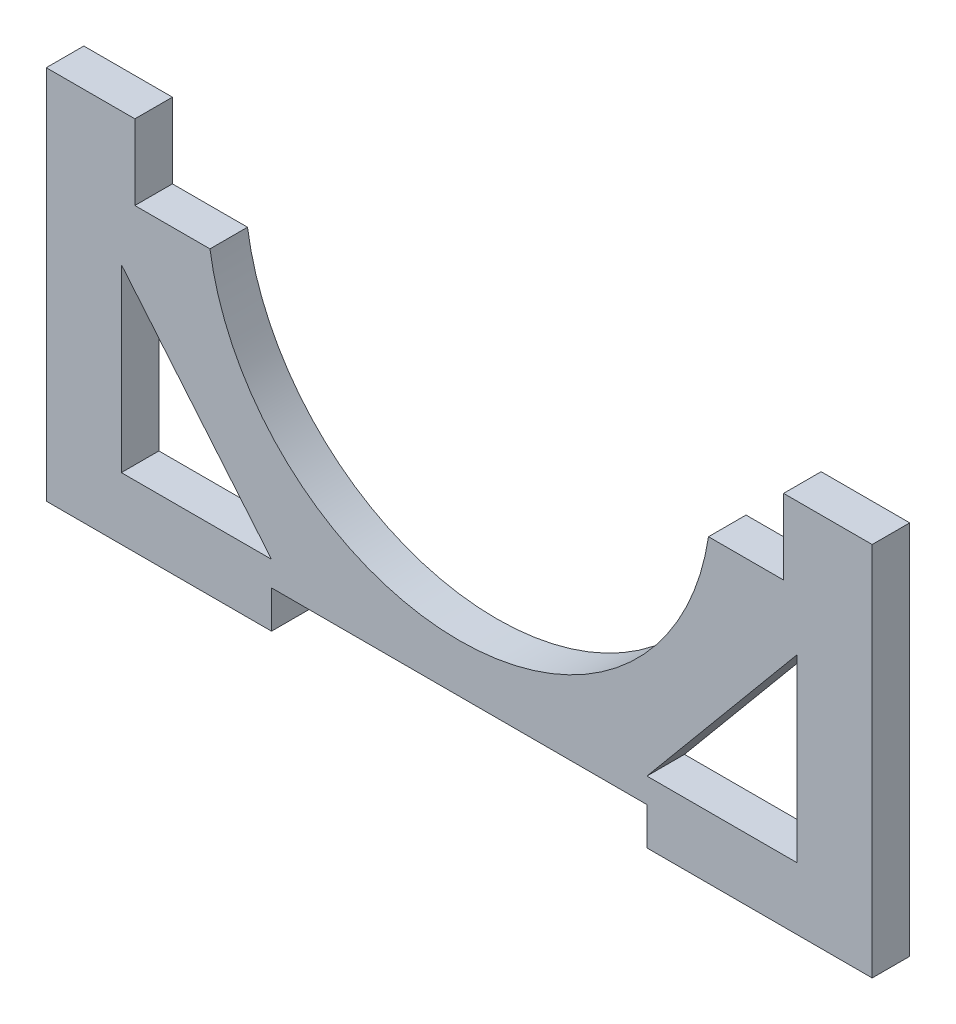
SolidWorks part; units mm, degrees
ref_plane "Front" through (0, 0, 0) normal (0, 0, 1) x (1, 0, 0)
ref_plane "Top" through (0, 0, 0) normal (0, 1, 0) x (1, 0, 0)
ref_plane "Right" through (0, 0, 0) normal (1, 0, 0) x (0, 0, -1)
sketch "Sketch1" plane through (0, 0, 0) normal (0, 0, 1) x (1, 0, 0)
  line L0 (-34.925, 28.575) -> (-34.925, -3.175)
  line L1 (-34.925, -3.175) -> (-15.875, -3.175)
  line L2 (-15.875, -3.175) -> (-15.875, 0)
  line L3 (-15.875, 0) -> (15.875, 0)
  line L4 (15.875, 0) -> (15.875, -3.175)
  line L5 (15.875, -3.175) -> (34.925, -3.175)
  line L6 (34.925, -3.175) -> (34.925, 28.575)
  line L7 (-34.925, 28.575) -> (-27.432, 28.575)
  line L8 (-27.432, 28.575) -> (-27.432, 22.225)
  line L9 (34.925, 28.575) -> (27.432, 28.575)
  line L10 (27.432, 28.575) -> (27.432, 22.225)
  line L11 (-27.432, 22.225) -> (27.432, 22.225)
  point P8 (81.2981, 37.8407)
  point P13 (0, 0)
  dimension "D1" = 31.75
  dimension "D2" = 19.05
  dimension "D3" = 3.175
  dimension "D4" = 22.225
  dimension "D5" = 6.35
  dimension "D6" = 54.864
extrude "Boss-Extrude1" add sketch "Sketch1" along normal blind 3.175
sketch "Sketch2" plane through (0, 0, 3.175) normal (0, 0, 1) x (1, 0, 0)
  line L0 (27.432, 22.225) -> (-27.432, 22.225) construction
  line L1 (-34.925, 28.575) -> (-34.925, -3.175) construction
  line L2 (-15.875, 0) -> (15.875, 0) construction
  line L3 (-21.082, 22.225) -> (21.082, 22.225)
  line L4 (27.432, 28.575) -> (27.432, 22.225) construction
  line L5 (-27.432, 22.225) -> (-27.432, 28.575) construction
  line L6 (-28.575, 17.3307) -> (-28.575, 2.0907)
  line L7 (-28.575, 2.0907) -> (-15.875, 2.0907)
  line L8 (-15.875, 2.0907) -> (-28.575, 17.3307)
  line L9 (0, 22.225) -> (0, 0.4433) construction
  line L10 (-34.925, -3.175) -> (-15.875, -3.175) construction
  line L11 (28.575, 2.0907) -> (15.875, 2.0907)
  line L12 (28.575, 17.3307) -> (28.575, 2.0907)
  line L13 (15.875, 2.0907) -> (28.575, 17.3307)
  arc A0 (-21.082, 22.225) -> (21.082, 22.225) centre (0, 25.4) ccw
  point P23 (28.2244, 28.8484)
  dimension "D1" = 25.4
  dimension "D2" = 6.35
  dimension "D3" = 6.35
  dimension "D4" = 5.2657
  dimension "D5" = 6.35
  dimension "D6" = 15.24
  dimension "D7" = 12.7
extrude "Cut-Extrude1" cut sketch "Sketch2" against normal through all
